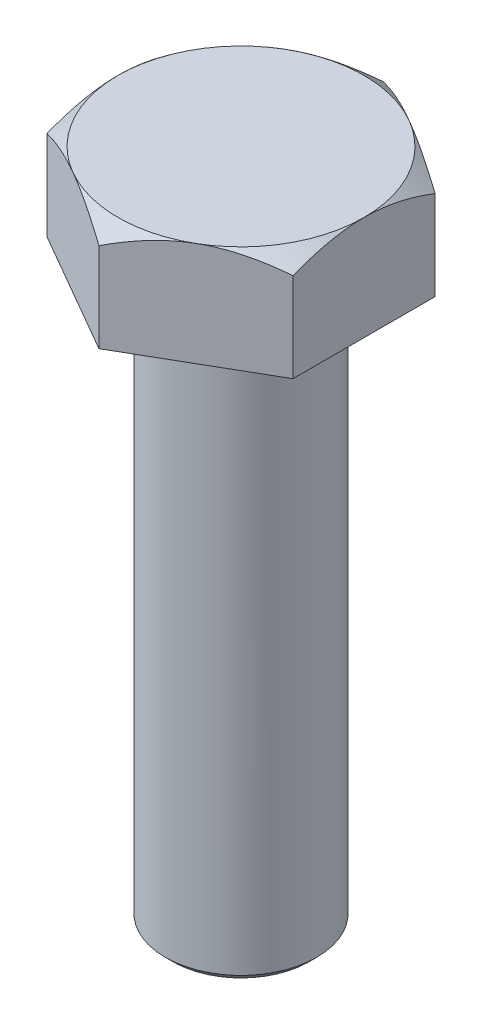
SolidWorks part; units mm, degrees
ref_plane "Front Plane" through (0, 0, 0) normal (0, 0, 1) x (1, 0, 0)
ref_plane "Top Plane" through (0, 0, 0) normal (0, 1, 0) x (1, 0, 0)
ref_plane "Right Plane" through (0, 0, 0) normal (1, 0, 0) x (0, 0, -1)
sketch "Sketch1" plane through (0, 0, 0) normal (0, 0, 1) x (1, 0, 0)
  line L0 (0, 0) -> (0, 48.0649) construction
  line L1 (0, 30) -> (-4, 30)
  line L2 (-4, 30) -> (-4, 0)
  line L3 (-4, 0) -> (0, 0)
  line L4 (0, 30) -> (0, 0)
  dimension "D1" = 30
  dimension "D2" = 4
revolve "Revolve1" add sketch "Sketch1" angle 360 about L4
sketch "Sketch2" plane through (0, 30, 0) normal (0, 1, 0) x (1, 0, 0)
  line L1 (0, -7.5056) -> (6.5, -3.7528)
  line L2 (6.5, -3.7528) -> (6.5, 3.7528)
  line L3 (6.5, 3.7528) -> (0, 7.5056)
  line L4 (0, 7.5056) -> (-6.5, 3.7528)
  line L5 (-6.5, 3.7528) -> (-6.5, -3.7528)
  line L6 (-6.5, -3.7528) -> (0, -7.5056)
  circle A0 centre (0, 0) radius 6.5 construction
  point P1 (0, 0)
  dimension "D1" = 13
extrude "Boss-Extrude1" add sketch "Sketch2" along normal blind 5.5
fillet "Fillet1" radius 0.4 1 edges at (0, 30, 4)
chamfer "Chamfer1" distance 0.4 angle 45 1 edges at (0, 0, 4)
sketch "Sketch3" plane through (0, 35.5, 0) normal (0, 1, 0) x (1, 0, 0)
  line L0 (0, 7.5056) -> (-6.5, 3.7528) construction
  circle A0 centre (0, 0) radius 6.5
extrude "Cut-Extrude1" cut sketch "Sketch3" against normal blind 1 draft 52 flip side to cut
